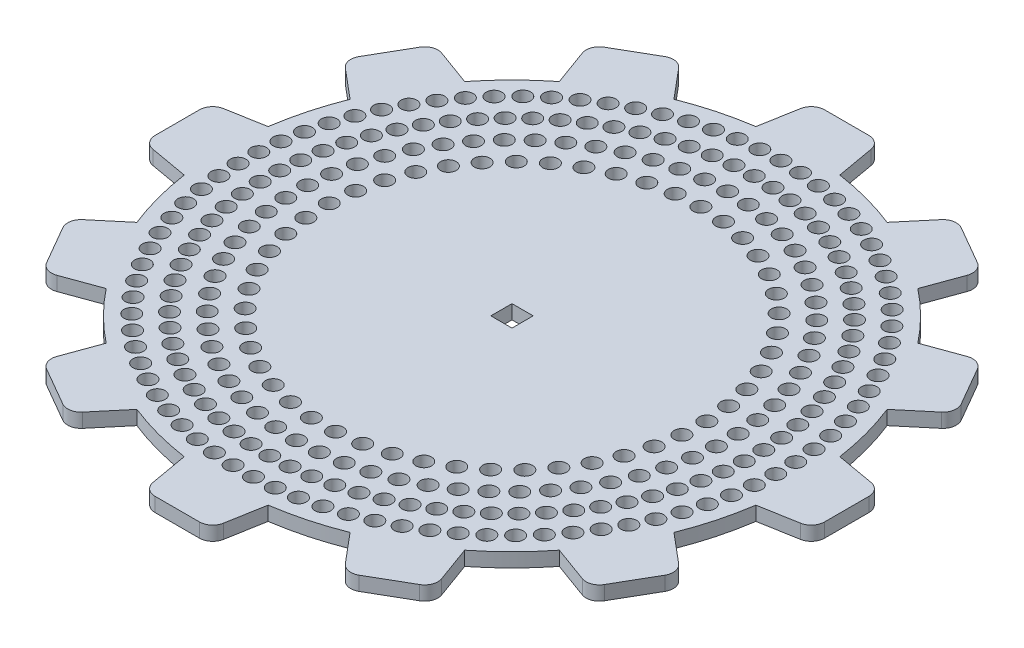
SolidWorks part; units mm, degrees
material "Balsa"
ref_plane "Front Plane" through (0, 0, 0) normal (0, 0, 1) x (1, 0, 0)
ref_plane "Top Plane" through (0, 0, 0) normal (0, 1, 0) x (1, 0, 0)
ref_plane "Right Plane" through (0, 0, 0) normal (1, 0, 0) x (0, 0, -1)
sketch "Sketch1" plane through (0, 0, 0) normal (0, 1, 0) x (1, 0, 0)
  line L1 (-4.7625, 4.7625) -> (4.7625, 4.7625)
  line L2 (-4.7625, 4.7625) -> (-4.7625, -4.7625)
  line L7 (-4.7625, -4.7625) -> (4.7625, -4.7625)
  line L8 (0, 121) -> (0, 109) construction
  line L9 (0, 109) -> (0, 97) construction
  line L10 (0, 97) -> (0, 85) construction
  line L11 (4.7625, 4.7625) -> (4.7625, -4.7625)
  line L12 (-4.7625, 4.7625) -> (4.7625, -4.7625) construction
  line L13 (-4.7625, -4.7625) -> (4.7625, 4.7625) construction
  circle A0 centre (0, 0) radius 130
  circle A39 centre (0, 85) radius 3.5
  circle A40 centre (0, 97) radius 3.5
  circle A41 centre (0, 109) radius 3.5
  circle A42 centre (0, 121) radius 3.5
  circle A43 centre (9.1511, 120.6535) radius 3.5
  circle A44 centre (18.2497, 119.6158) radius 3.5
  circle A45 centre (27.2439, 117.8931) radius 3.5
  circle A46 centre (36.0819, 115.495) radius 3.5
  circle A47 centre (44.7134, 112.4354) radius 3.5
  circle A48 centre (53.0886, 108.7318) radius 3.5
  circle A49 centre (61.1598, 104.4053) radius 3.5
  circle A50 centre (68.8807, 99.4809) radius 3.5
  circle A51 centre (76.2071, 93.9866) radius 3.5
  circle A52 centre (83.0969, 87.954) radius 3.5
  circle A53 centre (89.5108, 81.4176) radius 3.5
  circle A54 centre (95.4119, 74.4148) radius 3.5
  circle A55 centre (100.7666, 66.9858) radius 3.5
  circle A56 centre (105.544, 59.1731) radius 3.5
  circle A57 centre (109.7169, 51.0215) radius 3.5
  circle A58 centre (113.2614, 42.5776) radius 3.5
  circle A59 centre (116.1571, 33.8898) radius 3.5
  circle A60 centre (118.3875, 25.008) radius 3.5
  circle A61 centre (119.9398, 15.9828) radius 3.5
  circle A62 centre (120.805, 6.8662) radius 3.5
  circle A63 centre (120.9783, -2.2898) radius 3.5
  circle A64 centre (120.4587, -11.4327) radius 3.5
  circle A65 centre (119.249, -20.5101) radius 3.5
  circle A66 centre (117.3564, -29.47) radius 3.5
  circle A67 centre (114.7915, -38.2611) radius 3.5
  circle A68 centre (111.5691, -46.8331) radius 3.5
  circle A69 centre (107.7076, -55.1368) radius 3.5
  circle A70 centre (103.2292, -63.1247) radius 3.5
  circle A71 centre (98.1596, -70.751) radius 3.5
  circle A72 centre (92.5276, -77.972) radius 3.5
  circle A73 centre (86.3657, -84.7465) radius 3.5
  circle A74 centre (79.7091, -91.0355) radius 3.5
  circle A75 centre (72.5959, -96.8031) radius 3.5
  circle A76 centre (65.0669, -102.0162) radius 3.5
  circle A77 centre (57.1652, -106.6449) radius 3.5
  circle A78 centre (48.936, -110.6628) radius 3.5
  circle A79 centre (40.4266, -114.0469) radius 3.5
  circle A80 centre (31.6856, -116.7777) radius 3.5
  circle A81 centre (22.7631, -118.8396) radius 3.5
  circle A82 centre (13.7102, -120.2208) radius 3.5
  circle A83 centre (4.5788, -120.9133) radius 3.5
  circle A84 centre (-4.5788, -120.9133) radius 3.5
  circle A85 centre (-13.7102, -120.2208) radius 3.5
  circle A86 centre (-22.7631, -118.8396) radius 3.5
  circle A87 centre (-31.6856, -116.7777) radius 3.5
  circle A88 centre (-40.4266, -114.0469) radius 3.5
  circle A89 centre (-48.936, -110.6628) radius 3.5
  circle A90 centre (-57.1652, -106.6449) radius 3.5
  circle A91 centre (-65.0669, -102.0162) radius 3.5
  circle A92 centre (-72.5959, -96.8031) radius 3.5
  circle A93 centre (-79.7091, -91.0355) radius 3.5
  circle A94 centre (-86.3657, -84.7465) radius 3.5
  circle A95 centre (-92.5276, -77.972) radius 3.5
  circle A96 centre (-98.1596, -70.751) radius 3.5
  circle A97 centre (-103.2292, -63.1247) radius 3.5
  circle A98 centre (-107.7076, -55.1368) radius 3.5
  circle A99 centre (-111.5691, -46.8331) radius 3.5
  circle A100 centre (-114.7915, -38.2611) radius 3.5
  circle A101 centre (-117.3564, -29.47) radius 3.5
  circle A102 centre (-119.249, -20.5101) radius 3.5
  circle A103 centre (-120.4587, -11.4327) radius 3.5
  circle A104 centre (-120.9783, -2.2898) radius 3.5
  circle A105 centre (-120.805, 6.8662) radius 3.5
  circle A106 centre (-119.9398, 15.9828) radius 3.5
  circle A107 centre (-118.3875, 25.008) radius 3.5
  circle A108 centre (8.7709, 108.6465) radius 3.5
  circle A109 centre (17.4848, 107.5885) radius 3.5
  circle A110 centre (26.0854, 105.8327) radius 3.5
  circle A111 centre (34.5168, 103.3905) radius 3.5
  circle A112 centre (42.7244, 100.2778) radius 3.5
  circle A113 centre (50.6548, 96.5147) radius 3.5
  circle A114 centre (58.2568, 92.1257) radius 3.5
  circle A115 centre (65.4809, 87.1393) radius 3.5
  circle A116 centre (72.2804, 81.5877) radius 3.5
  circle A117 centre (78.6111, 75.507) radius 3.5
  circle A118 centre (84.4319, 68.9365) radius 3.5
  circle A119 centre (89.7052, 61.9191) radius 3.5
  circle A120 centre (94.3968, 54.5) radius 3.5
  circle A121 centre (98.4761, 46.7275) radius 3.5
  circle A122 centre (101.9168, 38.6519) radius 3.5
  circle A123 centre (104.6965, 30.3257) radius 3.5
  circle A124 centre (106.7972, 21.8028) radius 3.5
  circle A125 centre (108.2053, 13.1385) radius 3.5
  circle A126 centre (108.9116, 4.389) radius 3.5
  circle A127 centre (108.9116, -4.389) radius 3.5
  circle A128 centre (108.2053, -13.1385) radius 3.5
  circle A129 centre (106.7972, -21.8028) radius 3.5
  circle A130 centre (104.6965, -30.3257) radius 3.5
  circle A131 centre (101.9168, -38.6519) radius 3.5
  circle A132 centre (98.4761, -46.7275) radius 3.5
  circle A133 centre (94.3968, -54.5) radius 3.5
  circle A134 centre (89.7052, -61.9191) radius 3.5
  circle A135 centre (84.4319, -68.9365) radius 3.5
  circle A136 centre (78.6111, -75.507) radius 3.5
  circle A137 centre (72.2804, -81.5877) radius 3.5
  circle A138 centre (65.4809, -87.1393) radius 3.5
  circle A139 centre (58.2568, -92.1257) radius 3.5
  circle A140 centre (50.6548, -96.5147) radius 3.5
  circle A141 centre (42.7244, -100.2778) radius 3.5
  circle A142 centre (34.5168, -103.3905) radius 3.5
  circle A143 centre (26.0854, -105.8327) radius 3.5
  circle A144 centre (17.4848, -107.5885) radius 3.5
  circle A145 centre (8.7709, -108.6465) radius 3.5
  circle A146 centre (0, -109) radius 3.5
  circle A147 centre (-8.7709, -108.6465) radius 3.5
  circle A148 centre (-17.4848, -107.5885) radius 3.5
  circle A149 centre (-26.0854, -105.8327) radius 3.5
  circle A150 centre (-34.5168, -103.3905) radius 3.5
  circle A151 centre (-42.7244, -100.2778) radius 3.5
  circle A152 centre (-50.6548, -96.5147) radius 3.5
  circle A153 centre (-58.2568, -92.1257) radius 3.5
  circle A154 centre (-65.4809, -87.1393) radius 3.5
  circle A155 centre (-72.2804, -81.5877) radius 3.5
  circle A156 centre (-78.6111, -75.507) radius 3.5
  circle A157 centre (-84.4319, -68.9365) radius 3.5
  circle A158 centre (-89.7052, -61.9191) radius 3.5
  circle A159 centre (-94.3968, -54.5) radius 3.5
  circle A160 centre (-98.4761, -46.7275) radius 3.5
  circle A161 centre (-101.9168, -38.6519) radius 3.5
  circle A162 centre (9.8133, 96.5023) radius 3.5
  circle A163 centre (19.526, 95.0144) radius 3.5
  circle A164 centre (29.0382, 92.5515) radius 3.5
  circle A165 centre (38.2525, 89.1389) radius 3.5
  circle A166 centre (47.0743, 84.8116) radius 3.5
  circle A167 centre (55.413, 79.6141) radius 3.5
  circle A168 centre (63.1831, 73.5995) radius 3.5
  circle A169 centre (70.3049, 66.8298) radius 3.5
  circle A170 centre (76.7052, 59.3743) radius 3.5
  circle A171 centre (82.3185, 51.3095) radius 3.5
  circle A172 centre (87.087, 42.7182) radius 3.5
  circle A173 centre (90.962, 33.6886) radius 3.5
  circle A174 centre (93.9035, 24.3133) radius 3.5
  circle A175 centre (95.8814, 14.6885) radius 3.5
  circle A176 centre (96.8755, 4.913) radius 3.5
  circle A177 centre (96.8755, -4.913) radius 3.5
  circle A178 centre (95.8814, -14.6885) radius 3.5
  circle A179 centre (93.9035, -24.3133) radius 3.5
  circle A180 centre (90.962, -33.6886) radius 3.5
  circle A181 centre (87.087, -42.7182) radius 3.5
  circle A182 centre (82.3185, -51.3095) radius 3.5
  circle A183 centre (76.7052, -59.3743) radius 3.5
  circle A184 centre (70.3049, -66.8298) radius 3.5
  circle A185 centre (63.1831, -73.5995) radius 3.5
  circle A186 centre (55.413, -79.6141) radius 3.5
  circle A187 centre (47.0743, -84.8116) radius 3.5
  circle A188 centre (38.2525, -89.1389) radius 3.5
  circle A189 centre (29.0382, -92.5515) radius 3.5
  circle A190 centre (19.526, -95.0144) radius 3.5
  circle A191 centre (9.8133, -96.5023) radius 3.5
  circle A192 centre (0, -97) radius 3.5
  circle A193 centre (-9.8133, -96.5023) radius 3.5
  circle A194 centre (-19.526, -95.0144) radius 3.5
  circle A195 centre (-29.0382, -92.5515) radius 3.5
  circle A196 centre (-38.2525, -89.1389) radius 3.5
  circle A197 centre (-47.0743, -84.8116) radius 3.5
  circle A198 centre (-55.413, -79.6141) radius 3.5
  circle A199 centre (-63.1831, -73.5995) radius 3.5
  circle A200 centre (-70.3049, -66.8298) radius 3.5
  circle A201 centre (-76.7052, -59.3743) radius 3.5
  circle A202 centre (-82.3185, -51.3095) radius 3.5
  circle A203 centre (-87.087, -42.7182) radius 3.5
  circle A204 centre (-90.962, -33.6886) radius 3.5
  circle A205 centre (-93.9035, -24.3133) radius 3.5
  circle A206 centre (-95.8814, -14.6885) radius 3.5
  circle A207 centre (-96.8755, -4.913) radius 3.5
  circle A208 centre (-96.8755, 4.913) radius 3.5
  circle A209 centre (-95.8814, 14.6885) radius 3.5
  circle A210 centre (-93.9035, 24.3133) radius 3.5
  circle A211 centre (-90.962, 33.6886) radius 3.5
  circle A212 centre (-87.087, 42.7182) radius 3.5
  circle A214 centre (10.8696, 84.3022) radius 3.5
  circle A215 centre (21.5606, 82.2201) radius 3.5
  circle A216 centre (31.8977, 78.7879) radius 3.5
  circle A217 centre (41.711, 74.0621) radius 3.5
  circle A218 centre (50.8394, 68.1202) radius 3.5
  circle A219 centre (59.133, 61.0597) radius 3.5
  circle A220 centre (66.4557, 52.9966) radius 3.5
  circle A221 centre (72.6871, 44.0634) radius 3.5
  circle A222 centre (77.7251, 34.4066) radius 3.5
  circle A223 centre (81.4868, 24.1848) radius 3.5
  circle A224 centre (83.9105, 13.566) radius 3.5
  circle A225 centre (84.9563, 2.7244) radius 3.5
  circle A226 centre (84.6072, -8.162) radius 3.5
  circle A227 centre (82.8689, -18.9143) radius 3.5
  circle A228 centre (79.7698, -29.356) radius 3.5
  circle A229 centre (75.3609, -39.3158) radius 3.5
  circle A230 centre (69.7146, -48.6299) radius 3.5
  circle A231 centre (62.9236, -57.1456) radius 3.5
  circle A232 centre (55.0994, -64.7229) radius 3.5
  circle A233 centre (46.3705, -71.2375) radius 3.5
  circle A234 centre (36.8801, -76.5824) radius 3.5
  circle A235 centre (26.7842, -80.6697) radius 3.5
  circle A236 centre (16.2485, -83.4325) radius 3.5
  circle A237 centre (5.446, -84.8254) radius 3.5
  circle A238 centre (-5.446, -84.8254) radius 3.5
  circle A239 centre (-16.2485, -83.4325) radius 3.5
  circle A240 centre (-26.7842, -80.6697) radius 3.5
  circle A241 centre (-36.8801, -76.5824) radius 3.5
  circle A242 centre (-46.3705, -71.2375) radius 3.5
  circle A243 centre (-55.0994, -64.7229) radius 3.5
  circle A244 centre (-62.9236, -57.1456) radius 3.5
  circle A245 centre (-69.7146, -48.6299) radius 3.5
  circle A246 centre (-75.3609, -39.3158) radius 3.5
  circle A247 centre (-79.7698, -29.356) radius 3.5
  circle A248 centre (-82.8689, -18.9143) radius 3.5
  circle A249 centre (-84.6072, -8.162) radius 3.5
  circle A250 centre (-84.9563, 2.7244) radius 3.5
  circle A251 centre (-83.9105, 13.566) radius 3.5
  circle A252 centre (-81.4868, 24.1848) radius 3.5
  circle A253 centre (-77.7251, 34.4066) radius 3.5
  circle A254 centre (-72.6871, 44.0634) radius 3.5
  circle A255 centre (-66.4557, 52.9966) radius 3.5
  circle A256 centre (-59.133, 61.0597) radius 3.5
  circle A257 centre (-50.8394, 68.1202) radius 3.5
  circle A258 centre (-41.711, 74.0621) radius 3.5
  circle A259 centre (-31.8977, 78.7879) radius 3.5
  circle A260 centre (-21.5606, 82.2201) radius 3.5
  circle A261 centre (-10.8696, 84.3022) radius 3.5
  circle A262 centre (-82.3185, 51.3095) radius 3.5
  circle A263 centre (-76.7052, 59.3743) radius 3.5
  circle A264 centre (-70.3049, 66.8298) radius 3.5
  circle A265 centre (-63.1831, 73.5995) radius 3.5
  circle A266 centre (-55.413, 79.6141) radius 3.5
  circle A267 centre (-47.0743, 84.8116) radius 3.5
  circle A268 centre (-38.2525, 89.1389) radius 3.5
  circle A269 centre (-29.0382, 92.5515) radius 3.5
  circle A270 centre (-19.526, 95.0144) radius 3.5
  circle A271 centre (-9.8133, 96.5023) radius 3.5
  circle A272 centre (-104.6965, -30.3257) radius 3.5
  circle A273 centre (-106.7972, -21.8028) radius 3.5
  circle A274 centre (-108.2053, -13.1385) radius 3.5
  circle A275 centre (-108.9116, -4.389) radius 3.5
  circle A276 centre (-108.9116, 4.389) radius 3.5
  circle A277 centre (-108.2053, 13.1385) radius 3.5
  circle A278 centre (-106.7972, 21.8028) radius 3.5
  circle A279 centre (-104.6965, 30.3257) radius 3.5
  circle A280 centre (-101.9168, 38.6519) radius 3.5
  circle A281 centre (-98.4761, 46.7275) radius 3.5
  circle A282 centre (-94.3968, 54.5) radius 3.5
  circle A283 centre (-89.7052, 61.9191) radius 3.5
  circle A284 centre (-84.4319, 68.9365) radius 3.5
  circle A285 centre (-78.6111, 75.507) radius 3.5
  circle A286 centre (-72.2804, 81.5877) radius 3.5
  circle A287 centre (-65.4809, 87.1393) radius 3.5
  circle A288 centre (-58.2568, 92.1257) radius 3.5
  circle A289 centre (-50.6548, 96.5147) radius 3.5
  circle A290 centre (-42.7244, 100.2778) radius 3.5
  circle A291 centre (-34.5168, 103.3905) radius 3.5
  circle A292 centre (-26.0854, 105.8327) radius 3.5
  circle A293 centre (-17.4848, 107.5885) radius 3.5
  circle A294 centre (-8.7709, 108.6465) radius 3.5
  circle A295 centre (-116.1571, 33.8898) radius 3.5
  circle A296 centre (-113.2614, 42.5776) radius 3.5
  circle A297 centre (-109.7169, 51.0215) radius 3.5
  circle A298 centre (-105.544, 59.1731) radius 3.5
  circle A299 centre (-100.7666, 66.9858) radius 3.5
  circle A300 centre (-95.4119, 74.4148) radius 3.5
  circle A301 centre (-89.5108, 81.4176) radius 3.5
  circle A302 centre (-83.0969, 87.954) radius 3.5
  circle A303 centre (-76.2071, 93.9866) radius 3.5
  circle A304 centre (-68.8807, 99.4809) radius 3.5
  circle A305 centre (-61.1598, 104.4053) radius 3.5
  circle A306 centre (-53.0886, 108.7318) radius 3.5
  circle A307 centre (-44.7134, 112.4354) radius 3.5
  circle A308 centre (-36.0819, 115.495) radius 3.5
  circle A309 centre (-27.2439, 117.8931) radius 3.5
  circle A310 centre (-18.2497, 119.6158) radius 3.5
  circle A311 centre (-9.1511, 120.6535) radius 3.5
  dimension "D2" = 12
  dimension "D3" = 260
  dimension "D4" = 85
  dimension "D12" = 7
  dimension "D5" = 9.525
  dimension "D8" = 83
  dimension "D9" = 78
  dimension "D10" = 62
  dimension "D11" = 49
extrude "Boss-Extrude1" add sketch "Sketch1" along normal blind 6.35
sketch "Sketch2" plane through (0, 6.35, 0) normal (0, 1, 0) x (1, 0, 0)
  line L0 (0, 0) -> (0, 202.4314) construction
  line L1 (0, 0) -> (-221.3243, 0) construction
  line L2 (0, 0) -> (223.2936, 0) construction
  line L3 (0, 150.6218) -> (15, 150.6218)
  line L4 (0, 150.6218) -> (-15, 150.6218)
  line L5 (-15, 150.6218) -> (-18.8792, 128.6218)
  line L6 (15, 150.6218) -> (18.8792, 128.6218)
  line L7 (62.3205, 137.9423) -> (47.9611, 120.8294)
  line L8 (75.3109, 130.4423) -> (88.3013, 122.9423)
  line L9 (75.3109, 130.4423) -> (62.3205, 137.9423)
  line L10 (88.3013, 122.9423) -> (80.6608, 101.9502)
  line L11 (122.9423, 88.3013) -> (101.9502, 80.6608)
  line L12 (130.4423, 75.3109) -> (137.9423, 62.3205)
  line L13 (130.4423, 75.3109) -> (122.9423, 88.3013)
  line L14 (137.9423, 62.3205) -> (120.8294, 47.9611)
  line L15 (150.6218, 15) -> (128.6218, 18.8792)
  line L16 (150.6218, 0) -> (150.6218, -15)
  line L17 (150.6218, 0) -> (150.6218, 15)
  line L18 (150.6218, -15) -> (128.6218, -18.8792)
  line L19 (137.9423, -62.3205) -> (120.8294, -47.9611)
  line L20 (130.4423, -75.3109) -> (122.9423, -88.3013)
  line L21 (130.4423, -75.3109) -> (137.9423, -62.3205)
  line L22 (122.9423, -88.3013) -> (101.9502, -80.6608)
  line L23 (88.3013, -122.9423) -> (80.6608, -101.9502)
  line L24 (75.3109, -130.4423) -> (62.3205, -137.9423)
  line L25 (75.3109, -130.4423) -> (88.3013, -122.9423)
  line L26 (62.3205, -137.9423) -> (47.9611, -120.8294)
  line L27 (15, -150.6218) -> (18.8792, -128.6218)
  line L28 (0, -150.6218) -> (-15, -150.6218)
  line L29 (0, -150.6218) -> (15, -150.6218)
  line L30 (-15, -150.6218) -> (-18.8792, -128.6218)
  line L31 (-62.3205, -137.9423) -> (-47.9611, -120.8294)
  line L32 (-75.3109, -130.4423) -> (-88.3013, -122.9423)
  line L33 (-75.3109, -130.4423) -> (-62.3205, -137.9423)
  line L34 (-88.3013, -122.9423) -> (-80.6608, -101.9502)
  line L35 (-122.9423, -88.3013) -> (-101.9502, -80.6608)
  line L36 (-130.4423, -75.3109) -> (-137.9423, -62.3205)
  line L37 (-130.4423, -75.3109) -> (-122.9423, -88.3013)
  line L38 (-137.9423, -62.3205) -> (-120.8294, -47.9611)
  line L39 (-150.6218, -15) -> (-128.6218, -18.8792)
  line L40 (-150.6218, 0) -> (-150.6218, 15)
  line L41 (-150.6218, 0) -> (-150.6218, -15)
  line L42 (-150.6218, 15) -> (-128.6218, 18.8792)
  line L43 (-137.9423, 62.3205) -> (-120.8294, 47.9611)
  line L44 (-130.4423, 75.3109) -> (-122.9423, 88.3013)
  line L45 (-130.4423, 75.3109) -> (-137.9423, 62.3205)
  line L46 (-122.9423, 88.3013) -> (-101.9502, 80.6608)
  line L47 (-88.3013, 122.9423) -> (-80.6608, 101.9502)
  line L48 (-75.3109, 130.4423) -> (-62.3205, 137.9423)
  line L49 (-75.3109, 130.4423) -> (-88.3013, 122.9423)
  line L50 (-62.3205, 137.9423) -> (-47.9611, 120.8294)
  arc A0 (18.8792, 128.6218) -> (-18.8792, 128.6218) centre (0, 0) ccw
  circle A1 centre (0, 0) radius 130 construction
  arc A2 (80.6608, 101.9502) -> (47.9611, 120.8294) centre (0, 0) ccw
  arc A3 (120.8294, 47.9611) -> (101.9502, 80.6608) centre (0, 0) ccw
  arc A4 (128.6218, -18.8792) -> (128.6218, 18.8792) centre (0, 0) ccw
  arc A5 (101.9502, -80.6608) -> (120.8294, -47.9611) centre (0, 0) ccw
  arc A6 (47.9611, -120.8294) -> (80.6608, -101.9502) centre (0, 0) ccw
  arc A7 (-18.8792, -128.6218) -> (18.8792, -128.6218) centre (0, 0) ccw
  arc A8 (-80.6608, -101.9502) -> (-47.9611, -120.8294) centre (0, 0) ccw
  arc A9 (-120.8294, -47.9611) -> (-101.9502, -80.6608) centre (0, 0) ccw
  arc A10 (-128.6218, 18.8792) -> (-128.6218, -18.8792) centre (0, 0) ccw
  arc A11 (-101.9502, 80.6608) -> (-120.8294, 47.9611) centre (0, 0) ccw
  arc A12 (-47.9611, 120.8294) -> (-80.6608, 101.9502) centre (0, 0) ccw
  point P70 (0, 0)
  dimension "D1" = 100
  dimension "D2" = 100
  dimension "D3" = 15
  dimension "D4" = 22
  dimension "D5" = 12
extrude "Boss-Extrude2" add sketch "Sketch2" against normal up to surface (6.35 mm away) up to face at (-50.8394, 0, -64.6202)
fillet "Fillet3" radius 6 23 edges at (88.3013, 3.175, -122.9423) (62.3205, 3.175, -137.9423) (137.9423, 3.175, -62.3205) (150.6218, 3.175, -15) (150.6218, 3.175, 15) (137.9423, 3.175, 62.3205) (122.9423, 3.175, 88.3013) (88.3013, 3.175, 122.9423) (62.3205, 3.175, 137.9423) (15, 3.175, 150.6218) (-15, 3.175, 150.6218) (-62.3205, 3.175, 137.9423) (-88.3013, 3.175, 122.9423) (-122.9423, 3.175, 88.3013) (-137.9423, 3.175, 62.3205) (-150.6218, 3.175, 15) (15, 3.175, -150.6218) (-15, 3.175, -150.6218) (-62.3205, 3.175, -137.9423) (-88.3013, 3.175, -122.9423) (-122.9423, 3.175, -88.3013) (-137.9423, 3.175, -62.3205) (-150.6218, 3.175, -15)
fillet "Fillet4" radius 6 1 edges at (122.9423, 3.175, -88.3013)
sketch "Sketch3" plane through (0, 6.35, 0) normal (0, 1, 0) x (1, 0, 0)
  circle A0 centre (0, 0) radius 50 construction
  circle A1 centre (0, 0) radius 37.5 construction
  text T0 "PARTHENOPE  |  WPI MUSICAL ROBOTICS A18  |  MATTHEW BISSON, JORDAN GROTZ, CESAR GUERRERO, MICHAEL SIDLER  |  "
  text T1 "DISK 2  |  10RPS  |  B4 (49 holes)  |  D#5 (62 holes)  |  G5 (78 holes)  |  G#5 (83 holes)  |  "
  dimension "D1" = 100
  dimension "D2" = 75
